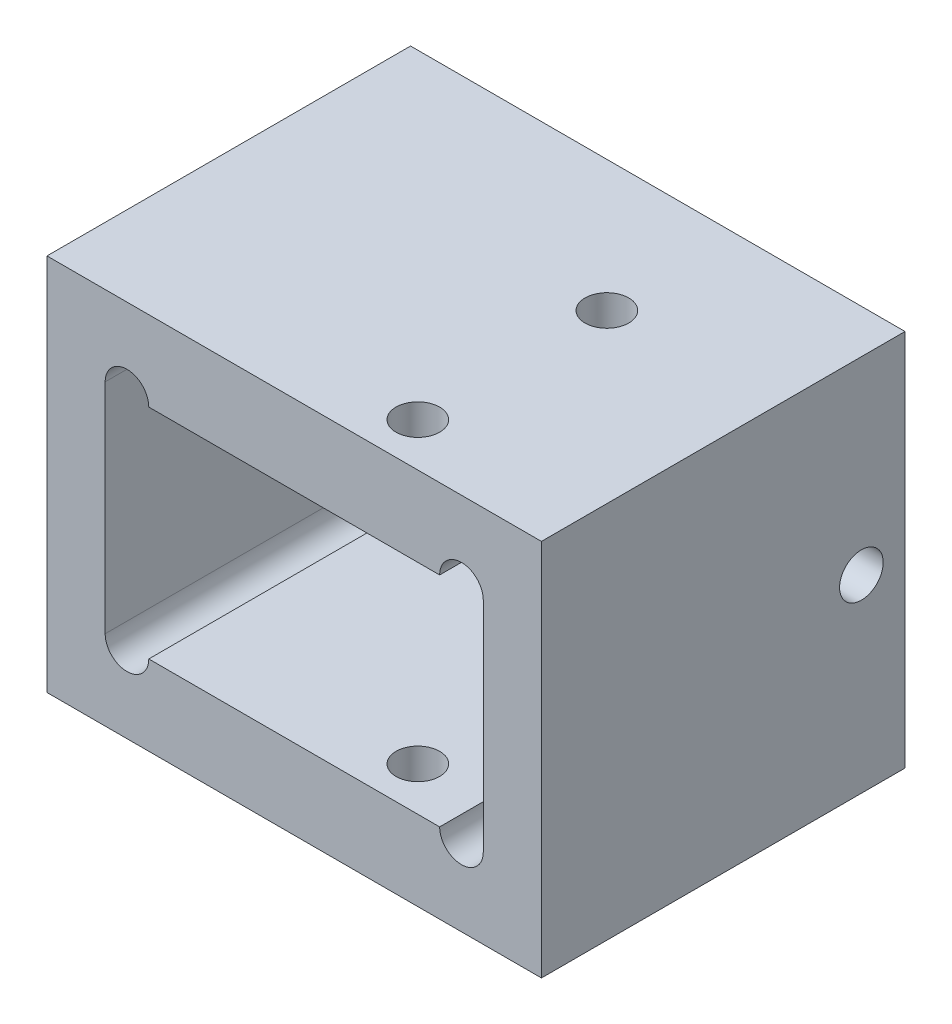
SolidWorks part; units mm, degrees
material "POM 乙缩醛共聚物"
ref_plane "前视基准面" through (0, 0, 0) normal (0, 0, 1) x (1, 0, 0)
ref_plane "上视基准面" through (0, 0, 0) normal (0, 1, 0) x (1, 0, 0)
ref_plane "右视基准面" through (0, 0, 0) normal (1, 0, 0) x (0, 0, -1)
sketch "草图1" plane through (0, 0, 0) normal (0, 0, 1) x (1, 0, 0)
  line L0 (0, 0) -> (66.141, 0) construction
  line L1 (0, -13) -> (0, 13)
  line L2 (0, 13) -> (34, 13)
  line L3 (0, -13) -> (34, -13)
  line L9 (34, 13) -> (34, -13)
  line L10 (4, -7.5) -> (4, 7.5)
  line L11 (4, 7.5) -> (30, 7.5)
  line L12 (4, -7.5) -> (30, -7.5)
  line L13 (30, 7.5) -> (30, -7.5)
  point P10 (4, 0)
  point P13 (30, 0)
  dimension "D1" = 26
  dimension "D2" = 5.5
  dimension "D3" = 34
  dimension "D4" = 4
  dimension "D5" = 4
extrude "凸台-拉伸1" add sketch "草图1" along normal blind 25
sketch "草图2" plane through (0, 0, 25) normal (0, 0, 1) x (1, 0, 0)
  line L0 (4, 0) -> (30, 0) construction
  line L3 (4, 7.5) -> (4, -7.5) construction
  line L4 (4, -7.5) -> (30, -7.5) construction
  line L5 (30, 7.5) -> (4, 7.5) construction
  line L6 (30, -7.5) -> (30, 7.5) construction
  line L7 (17, 0) -> (17, 7.5) construction
  circle A1 centre (5.5, 7.5) radius 1.5
  circle A2 centre (5.5, -7.5) radius 1.5
  circle A3 centre (28.5, -7.5) radius 1.5
  circle A4 centre (28.5, 7.5) radius 1.5
  point P15 (4, 0)
  dimension "D1" = 3
extrude "切除-拉伸1" cut sketch "草图2" against normal through all
sketch "草图3" plane through (0, 0, 0) normal (-1, 0, 0) x (0, 0, 1)
  line L0 (0, 0) -> (25, 0) construction
  line L1 (0, 13) -> (0, -13) construction
  line L2 (25, 13) -> (25, -13) construction
  circle A0 centre (10, 0) radius 2.5
  dimension "D1" = 5
  dimension "D2" = 10
extrude "切除-拉伸2" cut sketch "草图3" against normal up to surface (4 mm away) up to face at (4, 0, 12.5)
sketch "草图5" plane through (0, -7.5, 0) normal (0, 1, 0) x (1, 0, 0)
  line L0 (30, -22) -> (22.5, -22) construction
  line L2 (34, 0) -> (0, 0) construction
  line L3 (30, -25) -> (30, 0) construction
  circle A0 centre (22.5, -22) radius 1.5
  circle A1 centre (22.5, -9) radius 1.5
  point P2 (0, 0)
  point P8 (0, 0)
  dimension "D2" = 3
  dimension "D1" = 7.5
  dimension "D3" = 13
  dimension "D4" = 9
extrude "切除-拉伸4" cut sketch "草图5" against normal through all and the other way through all
sketch "草图6" plane through (34, 0, 0) normal (1, 0, 0) x (0, 0, -1)
  line L0 (-25, 0) -> (0, 0) construction
  line L1 (-25, -13) -> (-25, 13) construction
  circle A0 centre (-3, 0) radius 1.5
  dimension "D1" = 3
  dimension "D2" = 3
extrude "切除-拉伸5" cut sketch "草图6" against normal through all
